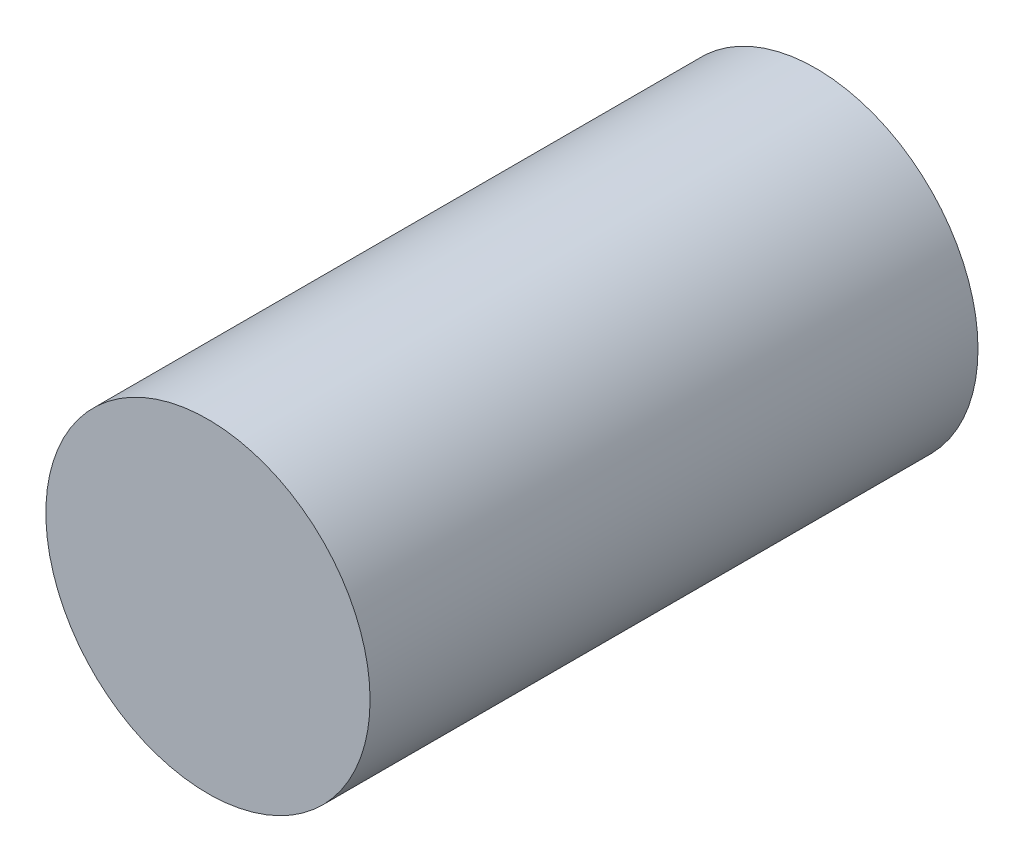
SolidWorks part; units mm, degrees
ref_plane "Front Plane" through (0, 0, 0) normal (0, 0, 1) x (1, 0, 0)
ref_plane "Top Plane" through (0, 0, 0) normal (0, 1, 0) x (1, 0, 0)
ref_plane "Right Plane" through (0, 0, 0) normal (1, 0, 0) x (0, 0, -1)
sketch "Sketch1" plane through (0, 0, 0) normal (0, 0, 1) x (1, 0, 0)
  circle A0 centre (0, 0) radius 40
  dimension "D1" = 80
extrude "Boss-Extrude1" add sketch "Sketch1" along normal blind 150
